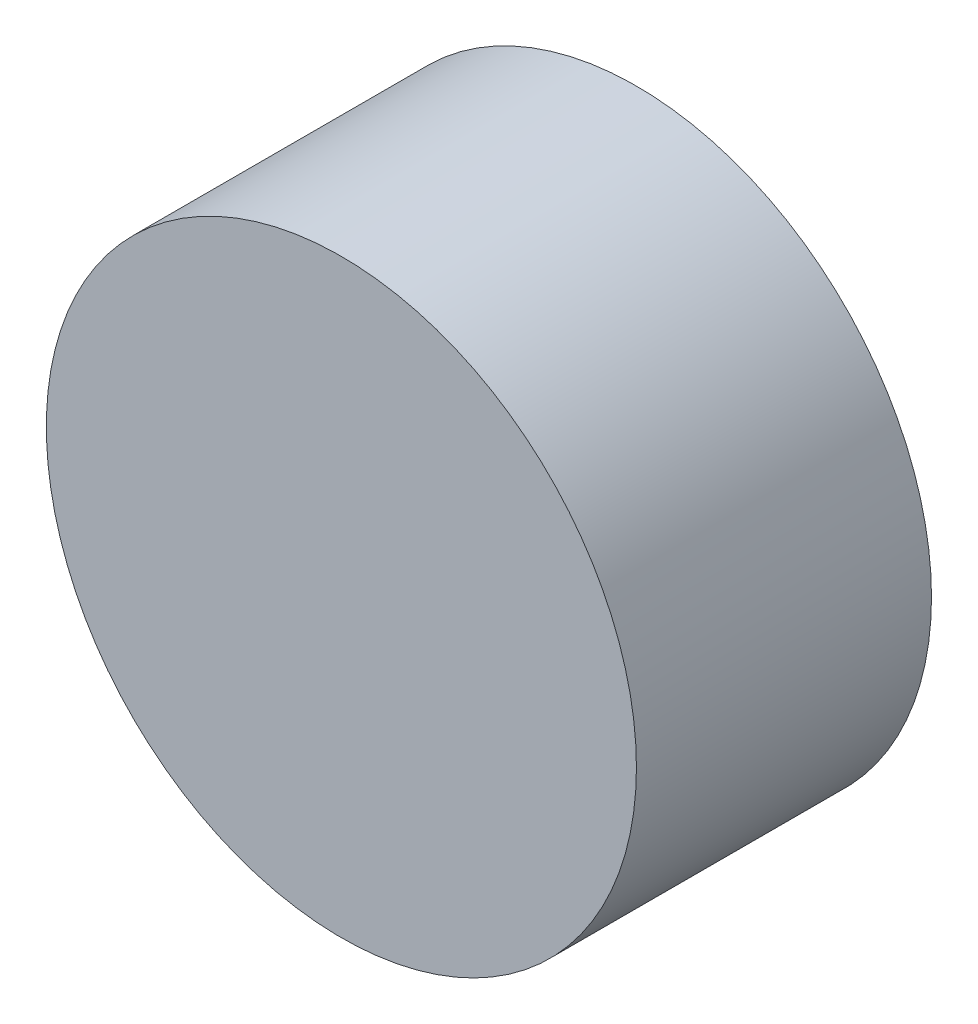
SolidWorks part; units mm, degrees
ref_plane "Front Plane" through (0, 0, 0) normal (0, 0, 1) x (1, 0, 0)
ref_plane "Top Plane" through (0, 0, 0) normal (0, 1, 0) x (1, 0, 0)
ref_plane "Right Plane" through (0, 0, 0) normal (1, 0, 0) x (0, 0, -1)
other "Center of Mass"
sketch "Sketch1" plane through (0, 0, 0) normal (0, 0, 1) x (1, 0, 0)
  circle A0 centre (0, 0) radius 100
  dimension "D1" = 200
extrude "Boss-Extrude1" add sketch "Sketch1" along normal blind 100
sketch "Sketch2" plane through (0, 0, 0) normal (0, 0, -1) x (-1, 0, 0)
  circle A0 centre (0, 0) radius 15
  dimension "D1" = 30
extrude "Cut-Extrude1" cut sketch "Sketch2" against normal blind 10
sketch "Sketch4" plane through (0, 0, 10) normal (0, 0, -1) x (-1, 0, 0)
  point P0 (0, 0)
